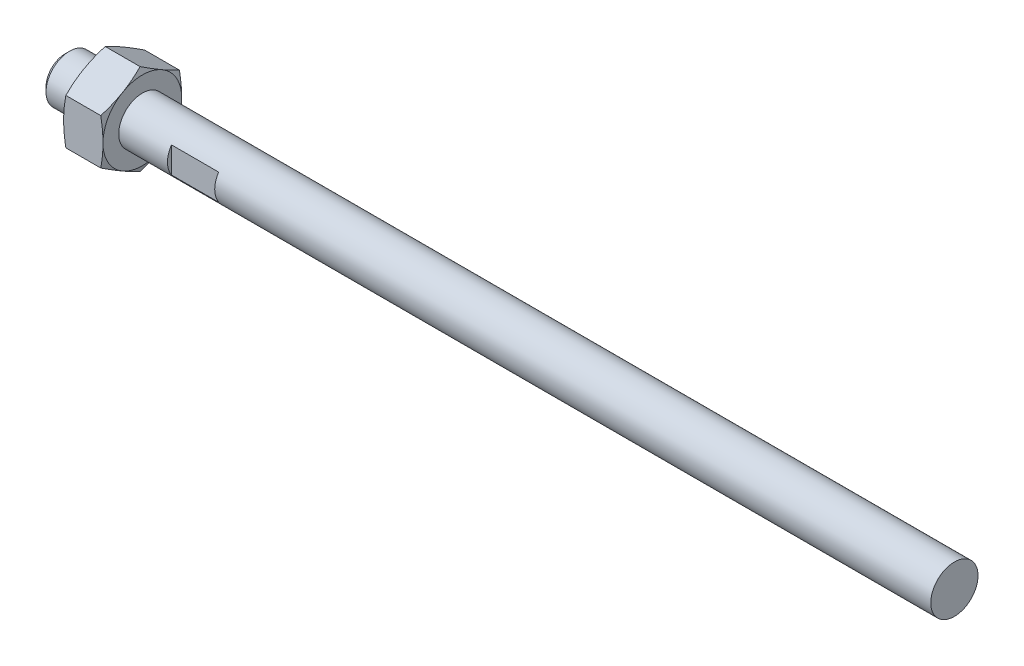
SolidWorks part; units mm, degrees
ref_plane "前视基准面" through (0, 0, 0) normal (0, 0, 1) x (1, 0, 0)
ref_plane "上视基准面" through (0, 0, 0) normal (0, 1, 0) x (1, 0, 0)
ref_plane "右视基准面" through (0, 0, 0) normal (1, 0, 0) x (0, 0, -1)
sketch "草图1" plane through (0, 0, 0) normal (0, 0, 1) x (1, 0, 0)
  line L0 (0, 0) -> (85, 0) construction
  line L1 (0, 0) -> (0, 25) construction
  line L2 (0, 25) -> (60, 25) construction
  line L3 (0, 0) -> (-16, 0) construction
  line L4 (-16, 8) -> (-16, -8) construction
  line L5 (85, 10.5) -> (85, -10.5) construction
  line L6 (-16, 0) -> (-38, 0) construction
  line L7 (-22, 3) -> (-22, -3) construction
  line L8 (-38, 3) -> (-38, -3) construction
  line L9 (85, 0) -> (101, 0) construction
  line L10 (94, 0) -> (94, 6) construction
  circle A0 centre (5, 0) radius 2.5
  point P3 (10, 0)
  point P6 (75, 0)
  point P7 (-2, 0)
  point P9 (-8, 0)
  point P12 (5, 0)
  point P17 (5, -8)
  point P19 (-22, 0)
  point P21 (-33.2, 0)
  point P22 (-28.2, 0)
  point P27 (94, 0)
  point P29 (87, 0)
  point P32 (97, 0)
  point P33 (101, 0)
  dimension "D4" = 4.8
  dimension "X" = 5
  dimension "D1" = 85
  dimension "行程" = 25
  dimension "C" = 60
  dimension "D2" = 5
  dimension "G" = 10
  dimension "D3" = 10
  dimension "F" = 16
  dimension "M" = 14
  dimension "AR" = 6
  dimension "L" = 16
  dimension "U" = 21
  dimension "Y" = 8
  dimension "V" = 6
  dimension "E" = 22
  dimension "H" = 16
  dimension "J" = 5
  dimension "K" = 6
  dimension "D" = 16
  dimension "S" = 9
  dimension "R" = 14
  dimension "P" = 6
  dimension "Q" = 12
  dimension "D1用" = 16
sketch "草图2" plane through (0, 0, 0) normal (1, 0, 0) x (0, 0, -1)
  line L0 (-2.5, 0) -> (2.5, 0) construction
  line L1 (-11, 0) -> (11, 0) construction
  line L2 (0, 0) -> (0, -8) construction
  line L3 (0, 12.5) -> (0, -12.5) construction
  line L4 (-11, 6.5628) -> (-11, -6.5628)
  line L5 (0, 12.5) -> (-11, 6.5628)
  line L6 (-11, -6.5628) -> (0, -12.5)
  line L7 (11, -6.5628) -> (0, -12.5)
  line L8 (11, 6.5628) -> (11, -6.5628)
  line L9 (0, 12.5) -> (11, 6.5628)
  line L10 (0, 8) -> (0, -8) construction
  line L11 (0, 5.7735) -> (-5, 2.8868)
  line L12 (-5, 2.8868) -> (-5, -2.8868)
  line L13 (-5, -2.8868) -> (0, -5.7735)
  line L14 (0, -5.7735) -> (5, -2.8868)
  line L15 (5, -2.8868) -> (5, 2.8868)
  line L16 (5, 2.8868) -> (0, 5.7735)
  line L17 (0, 10.5) -> (0, -10.5) construction
  line L18 (0, 0) -> (0, 25) construction
  circle A0 centre (0, 0) radius 5 construction
  circle A1 centre (0, 0) radius 11 construction
  dimension "AY" = 22
  dimension "I" = 10
  dimension "AX" = 25
  dimension "W" = 5
sketch "行程" plane through (0, 0, 0) normal (0, 0, 1) x (1, 0, 0)
  line L0 (75, 0) -> (50, 0)
  line L1 (0, 0) -> (85, 0) construction
  dimension "D1" = 25
sketch "草图3" plane through (0, 0, 0) normal (1, 0, 0) x (0, 0, -1)
  circle A0 centre (0, 0) radius 3
extrude "凸台-拉伸1" add sketch "草图3" along normal up to vertex (-22 mm away) from vertex at -38 starting at point (-38, 0, 0)
cosmetic thread "装饰螺纹线1" parameters "D2"=5.1
cosmetic thread "装饰螺纹线2" parameters "D1"=6.2, "D2"=5.1
sketch "草图4" plane through (0, 0, 0) normal (1, 0, 0) x (0, 0, -1)
  line L0 (0, -5.7735) -> (5, -2.8868) construction
  line L1 (5, -2.8868) -> (5, 2.8868) construction
  line L2 (5, 2.8868) -> (0, 5.7735) construction
  line L3 (0, 5.7735) -> (-5, 2.8868) construction
  line L4 (-5, 2.8868) -> (-5, -2.8868) construction
  line L5 (-5, -2.8868) -> (0, -5.7735) construction
  line L6 (0, -5.7735) -> (5, -2.8868)
  line L7 (5, -2.8868) -> (5, 2.8868)
  line L8 (5, 2.8868) -> (0, 5.7735)
  line L9 (0, 5.7735) -> (-5, 2.8868)
  line L10 (-5, 2.8868) -> (-5, -2.8868)
  line L11 (-5, -2.8868) -> (0, -5.7735)
extrude "凸台-拉伸2" add sketch "草图4" along normal up to vertex (-28.2 mm away) from vertex at -33.2 starting at point (-33.2, 0, 0)
sketch "草图5" plane through (-22, 0, 0) normal (1, 0, 0) x (0, 0, -1)
  circle A0 centre (0, 0) radius 3
extrude "凸台-拉伸3" add sketch "草图5" along normal up to vertex (97 mm away) up to point (75, 0, 0)
sketch "草图6" plane through (0, 0, 0) normal (1, 0, 0) x (0, 0, -1)
  line L0 (-2.5, 5.7735) -> (-2.5, -5.7735)
  line L1 (2.5, 5.7735) -> (2.5, -5.7735)
  line L2 (-2.5, 5.7735) -> (2.5, 5.7735)
  line L3 (-2.5, -5.7735) -> (2.5, -5.7735)
extrude "切除-拉伸1" cut sketch "草图6" along normal up to vertex (-16 mm away) from vertex at -22 flip side to cut starting at point (-22, 0, 0)
sketch "草图7" plane through (0, 0, 0) normal (0, 1, 0) x (1, 0, 0)
  line L0 (-33.2, 5) -> (-33.2, 16.8687)
  line L1 (-30.7, 5) -> (-30.7, 0) construction
  line L2 (-28.2, 5) -> (-33.2, 5) construction
  line L3 (-16, 0) -> (-38, 0) construction
  line L4 (-33.2, 5) -> (-30.7, 11.8687)
  line L5 (-28.2, 5) -> (-30.7, 11.8687)
  line L6 (-28.2, 5) -> (-28.2, 16.8687)
  line L7 (-33.2, 16.8687) -> (-28.2, 16.8687)
  dimension "D1" = 20
  dimension "D2" = 5
revolve "切除-旋转1" cut sketch "草图7" angle 360 mid plane about L6
chamfer "倒角1" distance 0.56 angle 45 1 edges at (-38, 0, -3)
